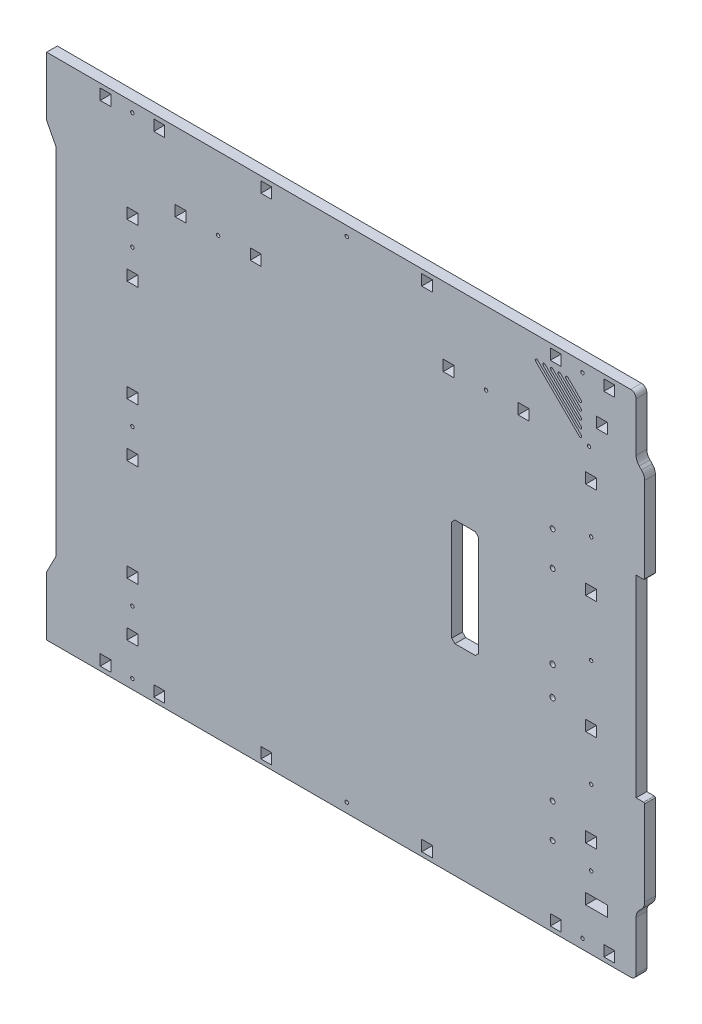
SolidWorks part; units mm, degrees
ref_plane "Front" through (0, 0, 0) normal (0, 0, 1) x (1, 0, 0)
ref_plane "Top" through (0, 0, 0) normal (0, 1, 0) x (1, 0, 0)
ref_plane "Right" through (0, 0, 0) normal (1, 0, 0) x (0, 0, -1)
sketch "Эскиз1" plane through (0, 0, 0) normal (0, 0, 1) x (1, 0, 0)
  line L0 (124, -47) -> (121, -50)
  line L1 (99, -47) -> (102, -50)
  line L2 (102, 50) -> (99, 47)
  line L3 (124, 47) -> (121, 50)
  line L4 (102, 50) -> (121, 50)
  line L5 (99, -47) -> (99, 47)
  line L6 (121, -50) -> (102, -50)
  line L7 (124, 47) -> (124, -47)
  line L8 (-204.0023, -55) -> (-193.9023, -55)
  line L9 (-204.0023, -45) -> (-204.0023, -55)
  line L10 (-193.9023, -45) -> (-204.0023, -45)
  line L11 (-193.9023, -55) -> (-193.9023, -45)
  line L12 (-204.0023, -5) -> (-193.9023, -5)
  line L13 (-204.0023, 5) -> (-204.0023, -5)
  line L14 (-193.9023, 5) -> (-204.0023, 5)
  line L15 (-193.9023, -5) -> (-193.9023, 5)
  line L16 (-79, 174.5) -> (-89, 174.5)
  line L17 (-79, 164.4) -> (-79, 174.5)
  line L18 (-89, 164.4) -> (-79, 164.4)
  line L19 (-89, 174.5) -> (-89, 164.4)
  line L20 (101, 174.5) -> (91, 174.5)
  line L21 (101, 164.4) -> (101, 174.5)
  line L22 (91, 164.4) -> (101, 164.4)
  line L23 (91, 174.5) -> (91, 164.4)
  line L24 (-149, 174.5) -> (-159, 174.5)
  line L25 (-149, 164.4) -> (-149, 174.5)
  line L26 (-159, 164.4) -> (-149, 164.4)
  line L27 (-159, 174.5) -> (-159, 164.4)
  line L28 (171, 174.5) -> (161, 174.5)
  line L29 (171, 164.4) -> (171, 174.5)
  line L30 (161, 164.4) -> (171, 164.4)
  line L31 (161, 174.5) -> (161, 164.4)
  line L32 (218.1465, 175.561) -> (177.2639, 215.9944)
  line L33 (179.0219, 217.7719) -> (219.9045, 177.3385)
  line L34 (217.9903, 203.8449) -> (205.5477, 216.1507)
  line L35 (207.3057, 217.9282) -> (219.7483, 205.6224)
  line L36 (218.1075, 182.632) -> (184.3349, 216.0335)
  line L37 (186.0928, 217.811) -> (219.8655, 184.4095)
  line L38 (218.0684, 189.7029) -> (191.4058, 216.0725)
  line L39 (193.1638, 217.85) -> (219.8264, 191.4804)
  line L40 (218.0294, 196.7739) -> (198.4768, 216.1116)
  line L41 (200.2348, 217.8891) -> (219.7873, 198.5514)
  line L42 (-279, 237.5) -> (266, 237.5)
  line L43 (-279, 182.5) -> (-279, 237.5)
  line L44 (-270.2697, 165.5) -> (-279, 182.5)
  line L45 (-270.2697, 165.5) -> (-270.2697, -165.5)
  line L46 (-279, -182.5) -> (-270.2697, -165.5)
  line L47 (-279, -237.5) -> (-279, -182.5)
  line L48 (266, -237.5) -> (-279, -237.5)
  line L49 (271, -186.6421) -> (271, -232.5)
  line L50 (276.0711, -177.4289) -> (273.9289, -179.5711)
  line L51 (279, -91) -> (279, -170.3579)
  line L52 (271, -90) -> (278, -90)
  line L53 (271, 90) -> (271, -90)
  line L54 (278, 90) -> (271, 90)
  line L55 (279, 170.3579) -> (279, 91)
  line L56 (273.9289, 179.5711) -> (276.0711, 177.4289)
  line L57 (271, 232.5) -> (271, 186.6421)
  line L58 (234.1, -50) -> (224, -50)
  line L59 (234.1, -60) -> (234.1, -50)
  line L60 (224, -60) -> (234.1, -60)
  line L61 (224, -50) -> (224, -60)
  line L62 (234.1, -140) -> (224, -140)
  line L63 (234.1, -150) -> (234.1, -140)
  line L64 (224, -150) -> (234.1, -150)
  line L65 (224, -140) -> (224, -150)
  line L66 (234, 200) -> (234, 190)
  line L67 (244.1, 200) -> (234, 200)
  line L68 (244.1, 190) -> (244.1, 200)
  line L69 (234, 190) -> (244.1, 190)
  line L70 (224, 60) -> (224, 50)
  line L71 (234.1, 60) -> (224, 60)
  line L72 (234.1, 50) -> (234.1, 60)
  line L73 (224, 50) -> (234.1, 50)
  line L74 (244.1, -190) -> (224, -190)
  line L75 (244.1, -200) -> (244.1, -190)
  line L76 (224, -200) -> (244.1, -200)
  line L77 (224, -190) -> (224, -200)
  line L78 (224, 150) -> (224, 140)
  line L79 (234.1, 150) -> (224, 150)
  line L80 (234.1, 140) -> (234.1, 150)
  line L81 (224, 140) -> (234.1, 140)
  line L82 (-179, -223.5) -> (-179, -233.6)
  line L83 (-169, -223.5) -> (-179, -223.5)
  line L84 (-169, -233.6) -> (-169, -223.5)
  line L85 (-179, -233.6) -> (-169, -233.6)
  line L86 (-169, 233.6) -> (-179, 233.6)
  line L87 (-169, 223.5) -> (-169, 233.6)
  line L88 (-179, 223.5) -> (-169, 223.5)
  line L89 (-179, 233.6) -> (-179, 223.5)
  line L90 (191, -223.5) -> (191, -233.6)
  line L91 (201, -223.5) -> (191, -223.5)
  line L92 (201, -233.6) -> (201, -223.5)
  line L93 (191, -233.6) -> (201, -233.6)
  line L94 (201, 233.6) -> (191, 233.6)
  line L95 (201, 223.5) -> (201, 233.6)
  line L96 (191, 223.5) -> (201, 223.5)
  line L97 (191, 233.6) -> (191, 223.5)
  line L98 (241, -223.5) -> (241, -233.6)
  line L99 (251, -223.5) -> (241, -223.5)
  line L100 (251, -233.6) -> (251, -223.5)
  line L101 (241, -233.6) -> (251, -233.6)
  line L102 (251, 233.6) -> (241, 233.6)
  line L103 (251, 223.5) -> (251, 233.6)
  line L104 (241, 223.5) -> (251, 223.5)
  line L105 (241, 233.6) -> (241, 223.5)
  line L106 (-79, -223.5) -> (-79, -233.6)
  line L107 (-69, -223.5) -> (-79, -223.5)
  line L108 (-69, -233.6) -> (-69, -223.5)
  line L109 (-79, -233.6) -> (-69, -233.6)
  line L110 (-69, 233.6) -> (-79, 233.6)
  line L111 (-69, 223.5) -> (-69, 233.6)
  line L112 (-79, 223.5) -> (-69, 223.5)
  line L113 (-79, 233.6) -> (-79, 223.5)
  line L114 (-219, 233.6) -> (-229, 233.6)
  line L115 (-219, 223.5) -> (-219, 233.6)
  line L116 (-229, 223.5) -> (-219, 223.5)
  line L117 (-229, 233.6) -> (-229, 223.5)
  line L118 (-229, -223.5) -> (-229, -233.6)
  line L119 (-219, -223.5) -> (-229, -223.5)
  line L120 (-219, -233.6) -> (-219, -223.5)
  line L121 (-229, -233.6) -> (-219, -233.6)
  line L122 (71, -223.5) -> (71, -233.6)
  line L123 (81, -223.5) -> (71, -223.5)
  line L124 (81, -233.6) -> (81, -223.5)
  line L125 (71, -233.6) -> (81, -233.6)
  line L126 (81, 233.6) -> (71, 233.6)
  line L127 (81, 223.5) -> (81, 233.6)
  line L128 (71, 223.5) -> (81, 223.5)
  line L129 (71, 233.6) -> (71, 223.5)
  line L130 (-193.9023, -200) -> (-193.9023, -190)
  line L131 (-204.0023, -200) -> (-193.9023, -200)
  line L132 (-204.0023, -190) -> (-204.0023, -200)
  line L133 (-193.9023, -190) -> (-204.0023, -190)
  line L134 (-193.9023, -150) -> (-193.9023, -140)
  line L135 (-204.0023, -150) -> (-193.9023, -150)
  line L136 (-204.0023, -140) -> (-204.0023, -150)
  line L137 (-193.9023, -140) -> (-204.0023, -140)
  line L138 (-204.0023, 90) -> (-193.9023, 90)
  line L139 (-204.0023, 100) -> (-204.0023, 90)
  line L140 (-193.9023, 100) -> (-204.0023, 100)
  line L141 (-193.9023, 90) -> (-193.9023, 100)
  line L142 (-204.0023, 140) -> (-193.9023, 140)
  line L143 (-204.0023, 150) -> (-204.0023, 140)
  line L144 (-193.9023, 150) -> (-204.0023, 150)
  line L145 (-193.9023, 140) -> (-193.9023, 150)
  circle A0 centre (193.0977, -48) radius 2.5
  circle A1 centre (193.0977, -21) radius 2.5
  circle A2 centre (193.0977, -131.5) radius 2.25
  circle A3 centre (193.0977, 56.5) radius 2.25
  circle A4 centre (193.0977, 88.5) radius 2.25
  circle A5 centre (193.0977, -163.5) radius 2.25
  circle A6 centre (-198.9523, -25) radius 1.6
  circle A7 centre (-119, 169.45) radius 1.6
  circle A8 centre (131, 169.45) radius 1.6
  circle A9 centre (229.05, 0) radius 1.6
  arc A10 (219.9045, 177.3385) -> (218.1465, 175.561) centre (219.0255, 176.4498) cw
  arc A11 (177.2639, 215.9944) -> (179.0219, 217.7719) centre (178.1429, 216.8832) cw
  arc A12 (219.7483, 205.6224) -> (217.9903, 203.8449) centre (218.8693, 204.7336) cw
  arc A13 (205.5477, 216.1507) -> (207.3057, 217.9282) centre (206.4267, 217.0394) cw
  arc A14 (219.8655, 184.4095) -> (218.1075, 182.632) centre (218.9865, 183.5207) cw
  arc A15 (184.3349, 216.0335) -> (186.0928, 217.811) centre (185.2138, 216.9222) cw
  arc A16 (219.8264, 191.4804) -> (218.0684, 189.7029) centre (218.9474, 190.5917) cw
  arc A17 (191.4058, 216.0725) -> (193.1638, 217.85) centre (192.2848, 216.9613) cw
  arc A18 (219.7873, 198.5514) -> (218.0294, 196.7739) centre (218.9083, 197.6626) cw
  arc A19 (198.4768, 216.1116) -> (200.2348, 217.8891) centre (199.3558, 217.0004) cw
  arc A20 (271, -232.5) -> (266, -237.5) centre (266, -232.5) cw
  arc A21 (271, -186.6421) -> (273.9289, -179.5711) centre (281, -186.6421) cw
  arc A22 (279, -170.3579) -> (276.0711, -177.4289) centre (269, -170.3579) cw
  arc A23 (278, -90) -> (279, -91) centre (278, -91) cw
  arc A24 (279, 91) -> (278, 90) centre (278, 91) cw
  arc A25 (276.0711, 177.4289) -> (279, 170.3579) centre (269, 170.3579) cw
  arc A26 (273.9289, 179.5711) -> (271, 186.6421) centre (281, 186.6421) cw
  arc A27 (266, 237.5) -> (271, 232.5) centre (266, 232.5) cw
  circle A28 centre (-198.9523, 120) radius 1.6
  circle A29 centre (-198.9523, -170) radius 1.6
  circle A30 centre (229.05, -170) radius 1.6
  circle A31 centre (221, -228.55) radius 1.6
  circle A32 centre (-199, 228.55) radius 1.6
  circle A33 centre (1, 228.55) radius 1.6
  circle A34 centre (221, 228.55) radius 1.6
  circle A35 centre (227.05, 172) radius 1.6
  circle A36 centre (229.05, -100) radius 1.6
  circle A37 centre (1, -228.55) radius 1.6
  circle A38 centre (-199, -228.55) radius 1.6
  circle A39 centre (229.05, 100) radius 1.6
extrude "Бобышка-Вытянуть1" add sketch "Эскиз1" along normal blind 10
